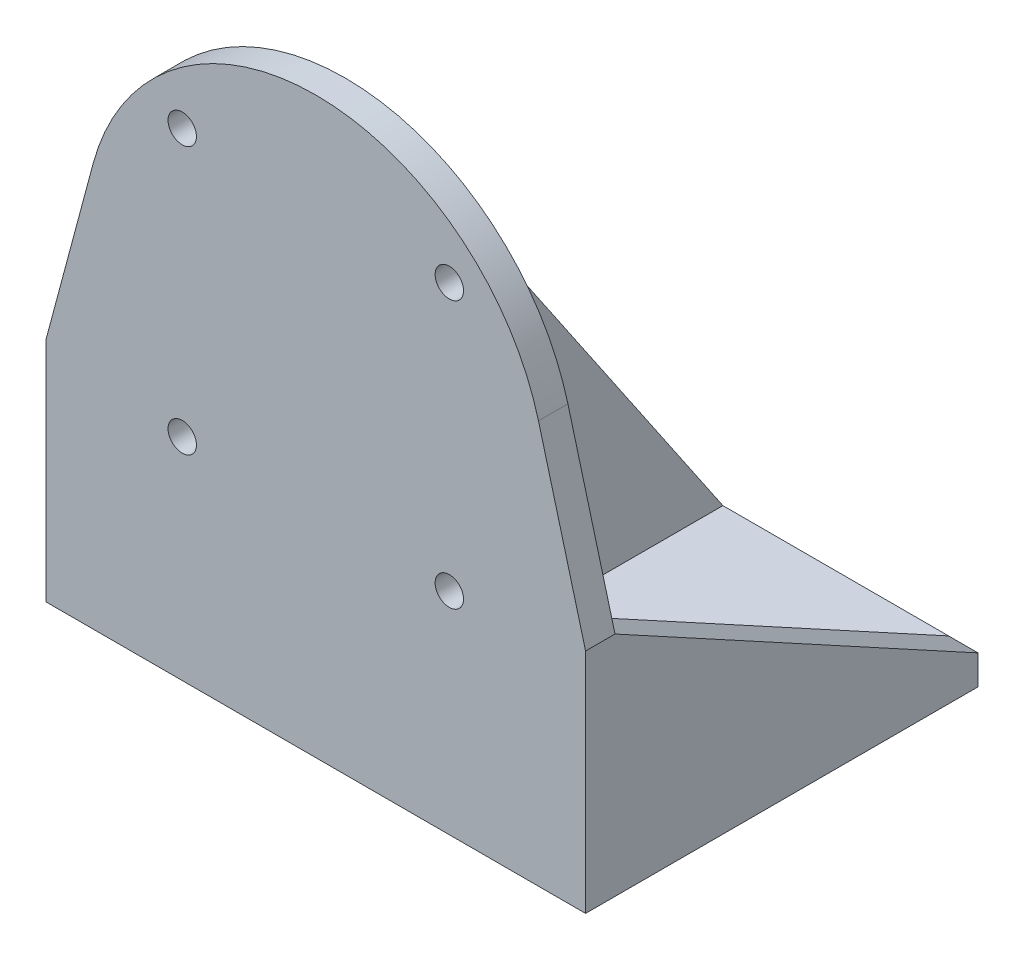
SolidWorks part; units mm, degrees
ref_plane "前视基准面" through (0, 0, 0) normal (0, 0, 1) x (1, 0, 0)
ref_plane "上视基准面" through (0, 0, 0) normal (0, 1, 0) x (1, 0, 0)
ref_plane "右视基准面" through (0, 0, 0) normal (1, 0, 0) x (0, 0, -1)
other "Configuration Table"
sketch "草图1" plane through (0, 0, 0) normal (0, 0, 1) x (1, 0, 0)
  line L0 (0, 0) -> (0, -7.9871) construction
  line L1 (0, -27.224) -> (27.224, -27.224) construction
  line L2 (27.224, 0) -> (27.224, -27.488) construction
  line L3 (-13.888, -25.5783) -> (-13.888, -48.744)
  line L4 (13.612, -13.744) -> (13.612, 6.8594) construction
  line L5 (36.3113, -7.6617) -> (41.112, -25.5783)
  line L6 (-9.0873, -7.6617) -> (-13.888, -25.5783)
  line L7 (41.112, -25.5783) -> (41.112, -48.744)
  line L8 (-13.888, -48.744) -> (41.112, -48.744)
  circle A0 centre (0, 0) radius 1.4478
  circle A1 centre (27.224, 0) radius 1.4478
  circle A2 centre (0, -27.224) radius 1.4478
  circle A3 centre (27.224, -27.224) radius 1.4478
  arc A4 (-9.0873, -7.6617) -> (36.3113, -7.6617) centre (13.612, -13.744) cw
  dimension "D1" = 2.8955
  dimension "D3" = 27.224
  dimension "D5" = 27.224
  dimension "D6" = 23.5
  dimension "D7" = 18.5486
  dimension "D8" = 23.1656
  dimension "D2" = 2
  dimension "D4" = 2
extrude "凸台-拉伸1" add sketch "草图1" against normal blind 3
sketch "草图2" plane through (0, 0, -3) normal (0, 0, -1) x (-1, 0, 0)
  line L0 (-41.112, -45.744) -> (13.888, -45.744)
  line L1 (-41.112, -48.744) -> (-41.112, -25.5783) construction
  line L2 (13.888, -25.5783) -> (13.888, -48.744) construction
  line L3 (13.888, -48.744) -> (-41.112, -48.744) construction
  line L9 (-36.3113, -7.6617) -> (-41.112, -25.5783)
  line L10 (-41.112, -25.5783) -> (-41.112, -48.744)
  line L11 (-41.112, -48.744) -> (13.888, -48.744)
  line L12 (13.888, -48.744) -> (13.888, -25.5783)
  line L13 (13.888, -25.5783) -> (9.0873, -7.6617)
  line L15 (-41.112, -45.744) -> (-41.112, -48.744)
  line L16 (-41.112, -48.744) -> (13.888, -48.744)
  line L17 (13.888, -48.744) -> (13.888, -45.744)
  arc A1 (9.0873, -7.6617) -> (-36.3113, -7.6617) centre (-13.612, -13.744) ccw
  dimension "D1" = 3
  dimension "D2" = 0
extrude "凸台-拉伸2" add sketch "草图2" along normal blind 37
sketch "草图3" plane through (0, -45.744, 0) normal (0, 1, 0) x (1, 0, 0)
  line L0 (13.612, 40) -> (13.612, 3) construction
  line L2 (-13.888, 40) -> (41.112, 40) construction
  line L3 (36.3113, 3) -> (-9.0873, 3) construction
  line L4 (32.312, 13) -> (32.312, 30)
  line L5 (41.112, 40) -> (41.112, 3) construction
  line L6 (-13.888, 21.5) -> (41.112, 21.5) construction
  line L7 (-13.888, 40) -> (-13.888, 3) construction
  line L8 (32.312, 30) -> (30.712, 30) construction
  line L9 (29.112, 30) -> (29.112, 13)
  line L10 (-1.888, 30) -> (-1.888, 13)
  line L11 (-5.088, 13) -> (-5.088, 30)
  arc A0 (32.312, 30) -> (29.112, 30) centre (30.712, 30) ccw
  arc A3 (-5.088, 30) -> (-1.888, 30) centre (-3.488, 30) cw
  arc A4 (32.312, 13) -> (29.112, 13) centre (30.712, 13) cw
  arc A5 (-5.088, 13) -> (-1.888, 13) centre (-3.488, 13) ccw
  point P8 (32.312, 21.5)
  dimension "D1" = 8.8
  dimension "D2" = 1.6
extrude "切除-拉伸1" cut sketch "草图3" against normal blind 3
ref_plane "基准面1" through (41.112, 0, 0) normal (1, 0, 0) x (0, 0, -1)
sketch "草图4" plane through (41.112, 0, 0) normal (1, 0, 0) x (0, 0, -1)
  line L0 (40, -45.744) -> (3, -25.5783)
  line L1 (3, -45.744) -> (3, -25.5783) construction
  line L2 (3, -25.5783) -> (3, -7.6617) construction
  line L3 (3, -25.5783) -> (3, -45.744)
  line L4 (3, -45.744) -> (40, -45.744)
  dimension "D1" = 42.1385
extrude "凸台-拉伸3" add sketch "草图4" against normal blind 3
ref_plane "基准面2" through (13.612, 0, 0) normal (-1, 0, 0) x (0, 1, 0)
sketch "草图12" plane through (0, 0, -3) normal (0, 0, -1) x (-1, 0, 0)
  line L0 (-13.612, -13.744) -> (-13.612, 13.9999) construction
  line L1 (-13.612, -30.25) -> (-13.612, 30.25) construction
  line L2 (-13.612, 13.9999) -> (-13.612, -53.4393) construction
sketch "草图10" plane through (13.612, 0, 0) normal (-1, 0, 0) x (0, 1, 0)
  line L1 (-45.744, 40) -> (-45.744, 3) construction
  line L2 (-45.744, 40) -> (-25.5783, 3) construction
  line L4 (-45.744, 40) -> (-45.744, 3)
sketch "草图13" plane through (13.612, 0, 0) normal (-1, 0, 0) x (0, 1, 0)
  line L0 (-45.744, 40) -> (8.756, 3)
  line L1 (13.9999, 3) -> (-53.4393, 3) construction
  line L2 (-45.744, 40) -> (-45.744, 3)
  line L3 (-45.744, 3) -> (8.756, 3)
  dimension "D1" = 65.873
extrude "凸台-拉伸4" add sketch "草图13" along normal blind 1.5 and the other way blind 1.5
mirror "镜向1" about plane through (13.612, 0, 0) normal (-1, 0, 0) of "凸台-拉伸3"
